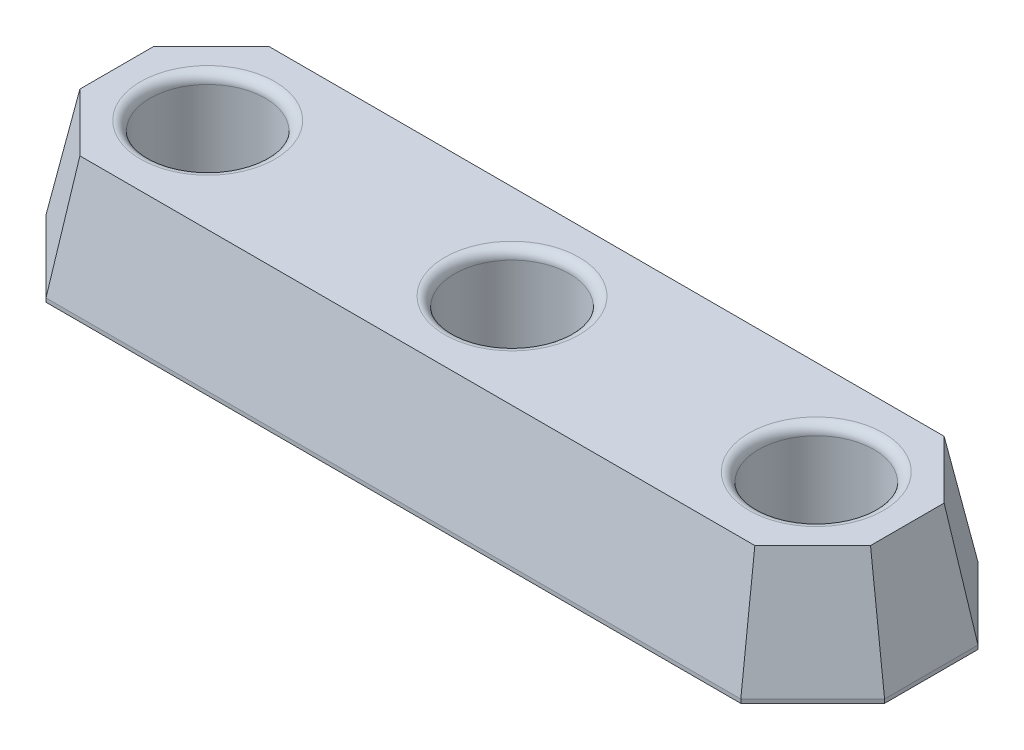
SolidWorks part; units mm, degrees
ref_plane "Front Plane" through (0, 0, 0) normal (0, 0, 1) x (1, 0, 0)
ref_plane "Top Plane" through (0, 0, 0) normal (0, 1, 0) x (1, 0, 0)
ref_plane "Right Plane" through (0, 0, 0) normal (1, 0, 0) x (0, 0, -1)
sketch "Sketch1" plane through (0, 0, 0) normal (0, 1, 0) x (1, 0, 0)
  line L0 (0, 4.95) -> (35, 4.95) construction
  line L1 (0, 0) -> (35, 0)
  line L2 (0, 0) -> (0, 9.9)
  line L3 (0, 9.9) -> (35, 9.9)
  line L4 (35, 0) -> (35, 9.9)
  line L6 (15.8, 3.25) -> (19.2, 3.25) construction
  line L7 (15.8, 3.25) -> (15.8, 6.65) construction
  line L8 (15.8, 6.65) -> (19.2, 6.65) construction
  line L9 (19.2, 3.25) -> (19.2, 6.65) construction
  line L10 (15.8, 3.25) -> (19.2, 6.65) construction
  line L11 (15.8, 6.65) -> (19.2, 3.25) construction
  circle A0 centre (4.8, 4.95) radius 2.4042
  circle A1 centre (17.5, 4.95) radius 2.4042
  circle A2 centre (30.2, 4.95) radius 2.4042
  dimension "D5" = 3.4
  dimension "D1" = 9.9
  dimension "D2" = 35
  dimension "D3" = 12.7
  dimension "D4" = 12.7
extrude "Boss-Extrude1" add sketch "Sketch1" along normal blind 5
chamfer "Chamfer1" distance 3 angle 45 4 edges at (35, 2.5, 0) (35, 2.5, -9.9) (0, 2.5, -9.9) (0, 2.5, 0)
chamfer "Chamfer2" distance 4.84 distance2 1 8 edges at (33.5, 5, -8.4) (35, 5, -4.95) (33.5, 5, -1.5) (17.5, 5, 0) (1.5, 5, -1.5) (0, 5, -4.95) (1.5, 5, -8.4) (17.5, 5, -9.9)
fillet "Fillet1" radius 0.4 6 edges at (30.2, 0, -2.5458) (17.5, 0, -2.5458) (4.8, 0, -2.5458) (4.8, 5, -2.5458) (17.5, 5, -2.5458) (30.2, 5, -2.5458)
